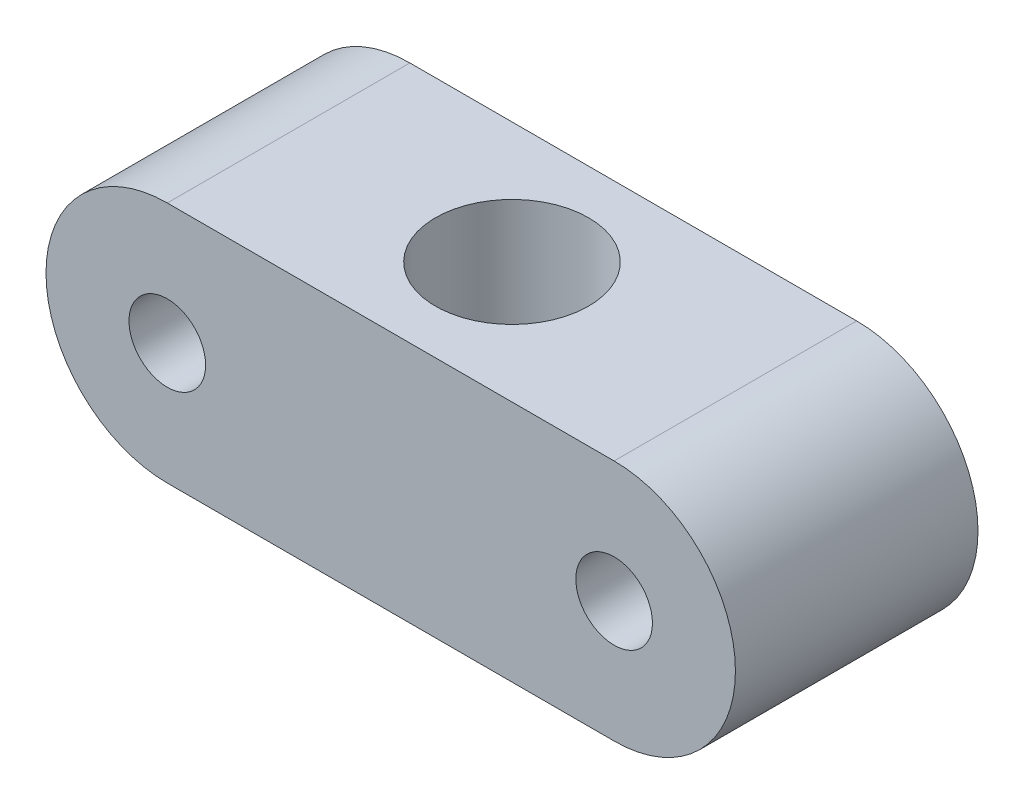
SolidWorks part; units mm, degrees
ref_plane "Front Plane" through (0, 0, 0) normal (0, 0, 1) x (1, 0, 0)
ref_plane "Top Plane" through (0, 0, 0) normal (0, 1, 0) x (1, 0, 0)
ref_plane "Right Plane" through (0, 0, 0) normal (1, 0, 0) x (0, 0, -1)
sketch "Sketch1" plane through (0, 0, 0) normal (0, 0, 1) x (1, 0, 0)
  line L0 (0, 0) -> (70, 0) construction
  line L1 (0, 19) -> (70, 19)
  line L2 (0, -19) -> (70, -19)
  arc A0 (0, 19) -> (0, -19) centre (0, 0) ccw
  arc A1 (70, -19) -> (70, 19) centre (70, 0) ccw
  circle A2 centre (0, 0) radius 6
  circle A3 centre (70, 0) radius 6
  point P3 (35, 0)
  dimension "D2" = 19
  dimension "D3" = 12
  dimension "D4" = 12
  dimension "D1" = 70
extrude "Boss-Extrude1" add sketch "Sketch1" along normal mid plane 38
sketch "Sketch2" plane through (0, -19, 0) normal (0, -1, 0) x (1, 0, 0)
  line L0 (0, 19) -> (0, -19) construction
  circle A0 centre (35, 0) radius 12
  dimension "D1" = 24
  dimension "D2" = 35
extrude "Cut-Extrude1" cut sketch "Sketch2" against normal through all
cosmetic thread "Cosmetic Thread3" parameters "D1"=5, "D2"=72
cosmetic thread "Cosmetic Thread4" parameters "D1"=5, "D2"=72
